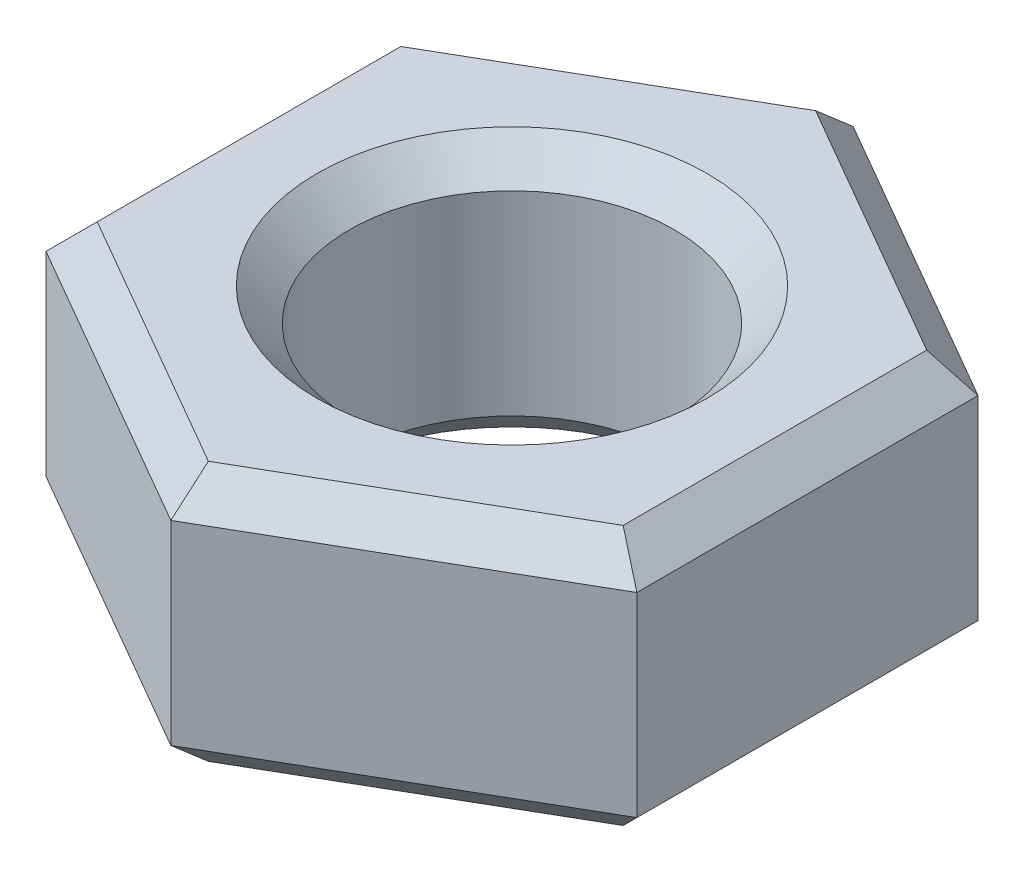
SolidWorks part; units mm, degrees
ref_plane "Plan de face" through (0, 0, 0) normal (0, 0, 1) x (1, 0, 0)
ref_plane "Plan de dessus" through (0, 0, 0) normal (0, 1, 0) x (1, 0, 0)
ref_plane "Plan de droite" through (0, 0, 0) normal (1, 0, 0) x (0, 0, -1)
sketch "Esquisse1" plane through (0, 0, 0) normal (0, 1, 0) x (1, 0, 0)
  line L1 (0, 3.15) -> (-2.728, 1.575)
  line L2 (-2.728, 1.575) -> (-2.728, -1.575)
  line L3 (-2.728, -1.575) -> (0, -3.15)
  line L4 (0, -3.15) -> (2.728, -1.575)
  line L5 (2.728, -1.575) -> (2.728, 1.575)
  line L6 (2.728, 1.575) -> (0, 3.15)
  circle A0 centre (0, 0) radius 2.728 construction
  circle A1 centre (0, 0) radius 1.5
  dimension "D1" = 3
  dimension "D2" = 6.3
extrude "Boss.-Extru.1" add sketch "Esquisse1" along normal blind 2.4
chamfer "Chanfrein1" distance 0.3 angle 45 14 edges at (0, 2.4, 1.5) (2.728, 2.4, 0) (1.364, 2.4, 2.3625) (-1.364, 2.4, 2.3625) (-2.728, 2.4, 0) (-1.364, 2.4, -2.3625) (1.364, 2.4, -2.3625) (0, 0, 1.5) (-1.364, 0, -2.3625) (-2.728, 0, 0) (-1.364, 0, 2.3625) (1.364, 0, 2.3625) (2.728, 0, 0) (1.364, 0, -2.3625)
